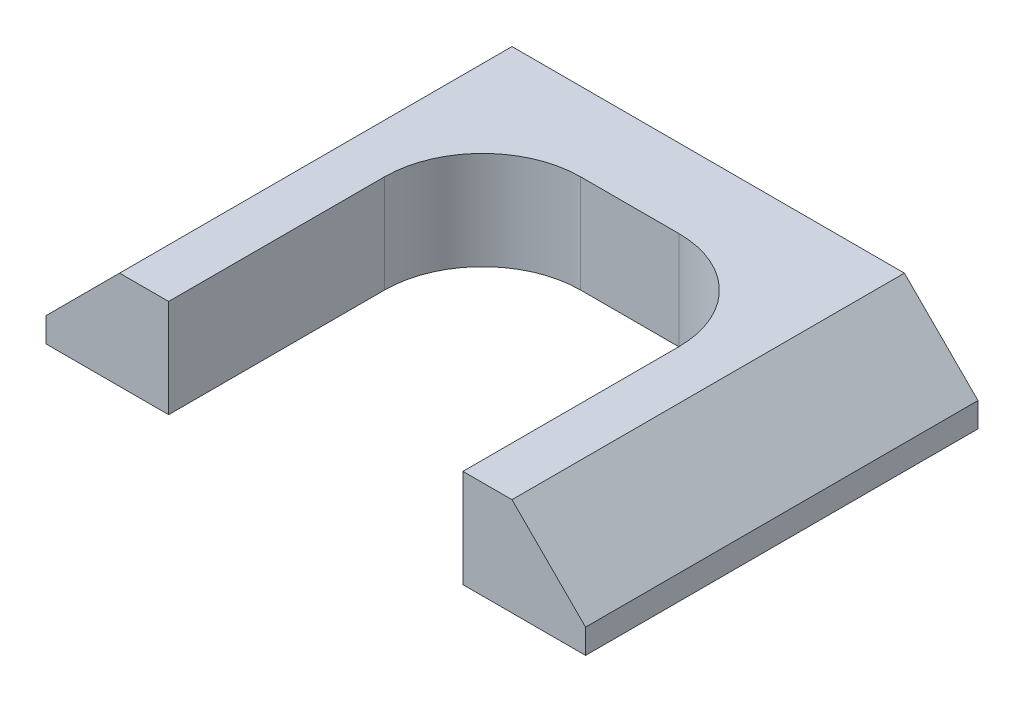
SolidWorks part; units mm, degrees
ref_plane "Front Plane" through (0, 0, 0) normal (0, 0, 1) x (1, 0, 0)
ref_plane "Top Plane" through (0, 0, 0) normal (0, 1, 0) x (1, 0, 0)
ref_plane "Right Plane" through (0, 0, 0) normal (1, 0, 0) x (0, 0, -1)
sketch "Sketch1" plane through (0, 0, 0) normal (0, 0, 1) x (1, 0, 0)
  line L0 (0, 0) -> (76.2, 0)
  line L1 (76.2, 0) -> (63.5, 12.7)
  line L2 (63.5, 12.7) -> (12.7, 12.7)
  line L3 (12.7, 12.7) -> (0, 0)
  dimension "D1" = 45
  dimension "D2" = 45
  dimension "D3" = 12.7
  dimension "D4" = 76.2
extrude "Boss-Extrude1" add sketch "Sketch1" along normal blind 50.8
sketch "Sketch2" plane through (0, 12.7, 0) normal (0, 1, 0) x (1, 0, 0)
  line L0 (63.5, -50.8) -> (12.7, -50.8) construction
  line L1 (19.05, -50.8) -> (57.15, -50.8)
  line L2 (19.05, -50.8) -> (19.05, -10.16)
  line L3 (19.05, -10.16) -> (57.15, -10.16)
  line L4 (57.15, -50.8) -> (57.15, -10.16)
  line L5 (38.1, 0) -> (38.1, -50.8) construction
  line L6 (63.5, 0) -> (12.7, 0) construction
  line L7 (12.7, -50.8) -> (12.7, 0) construction
  dimension "D1" = 40.64
  dimension "D2" = 6.35
extrude "Cut-Extrude1" cut sketch "Sketch2" against normal blind 76.2
fillet "Fillet1" radius 12.7 2 edges at (57.15, 6.35, 10.16) (19.05, 6.35, 10.16)
sketch "Sketch3" plane through (0, 0, 0) normal (0, 0, -1) x (-1, 0, 0)
  line L0 (0, 0) -> (-76.2, 0) construction
  line L1 (-73.025, 0) -> (-3.175, 0)
  line L2 (-73.025, 0) -> (-73.025, 12.7)
  line L3 (-73.025, 12.7) -> (-3.175, 12.7)
  line L4 (-3.175, 0) -> (-3.175, 12.7)
  line L5 (-63.5, 12.7) -> (-12.7, 12.7) construction
  line L6 (-38.1, 0) -> (-38.1, 12.7) construction
  dimension "D1" = 69.85
extrude "Cut-Extrude2" cut sketch "Sketch3" against normal through all flip side to cut
